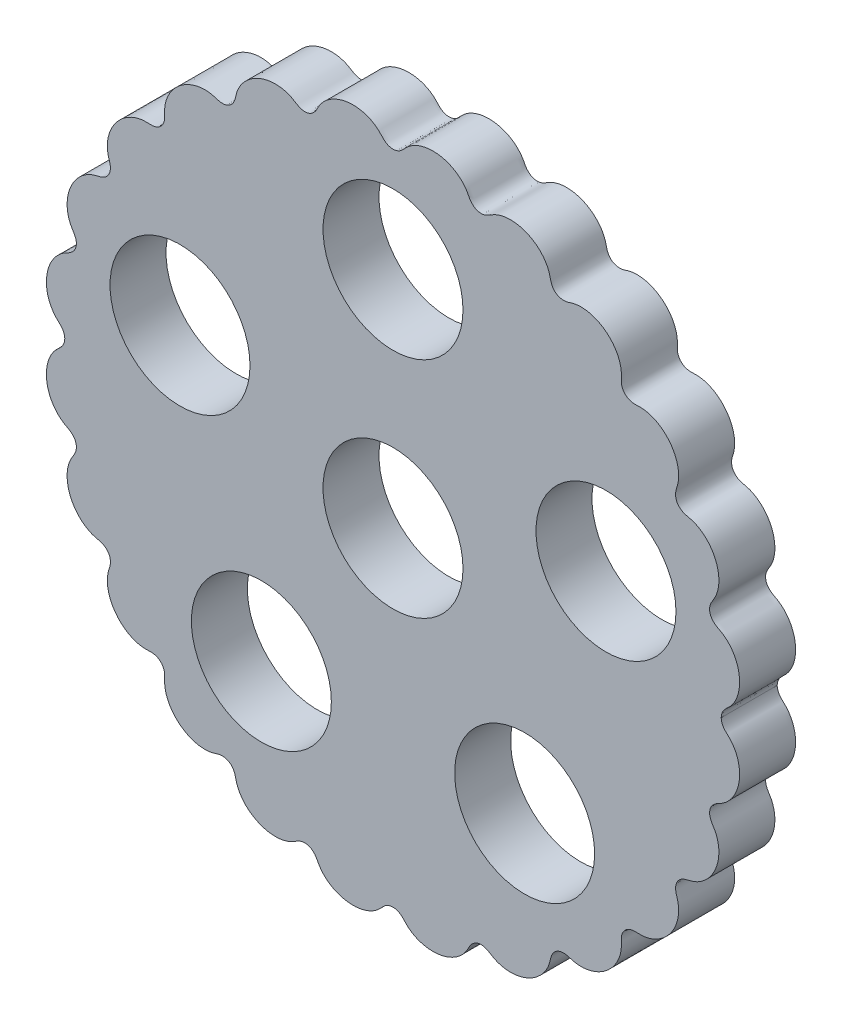
SolidWorks part; units mm, degrees
ref_plane "Plan de face" through (0, 0, 0) normal (0, 0, 1) x (1, 0, 0)
ref_plane "Plan de dessus" through (0, 0, 0) normal (0, 1, 0) x (1, 0, 0)
ref_plane "Plan de droite" through (0, 0, 0) normal (1, 0, 0) x (0, 0, -1)
sketch "Esquisse1" plane through (0, 0, 0) normal (0, 0, 1) x (1, 0, 0)
  line L0 (-1000, 0) -> (49000, 0) construction
  spline S0 degree 4 poles (22.9955, 6.6042) (22.9643, 6.5397) (22.914, 6.4032) (22.9023, 6.1862) (23.0214, 5.9244) (23.2219, 5.7605) (23.4288, 5.659) (23.6594, 5.5306) (23.9059, 5.3649) (24.1666, 5.1353) (24.4254, 4.835) (24.6422, 4.5029) (24.8162, 4.1468) (24.946, 3.7722) (25.0308, 3.385) (25.0698, 2.9906) (25.0624, 2.5943) (25.0079, 2.2017) (24.9068, 1.8224) (24.7781, 1.5066) (24.64, 1.2523) (24.5081, 1.0548) (24.3917, 0.9046) (24.2647, 0.7631) (24.1289, 0.6302) (24.012, 0.5251) (23.9248, 0.4355) (23.8688, 0.3622) (23.8363, 0.3122) (23.8082, 0.2597) (23.7852, 0.2044) (23.7697, 0.1547) (23.76, 0.1121) (23.7533, 0.0661) (23.7501, 0.0228) (23.7495, -0.004) (23.7513, -0.04) (23.7542, -0.0715) (23.7595, -0.1093) (23.7688, -0.1512) (23.7835, -0.1997) (23.8056, -0.2538) (23.8324, -0.3054) (23.8635, -0.3546) (23.9194, -0.4297) (24.009, -0.5227) (24.1313, -0.6322) (24.2737, -0.7721) (24.4392, -0.959) (24.6145, -1.2025) (24.7855, -1.5135) (24.9316, -1.8961) (25.0271, -2.299) (25.0708, -2.7153) (25.0622, -3.1311) (25.0033, -3.5401) (24.8958, -3.9363) (24.7419, -4.314) (24.5445, -4.6645) (24.307, -4.9822) (24.0331, -5.2614) (23.7654, -5.4667) (23.5164, -5.6129) (23.2956, -5.7243) (23.1195, -5.8363) (22.9763, -6.0087) (22.9044, -6.234) (22.925, -6.462) (23.0164, -6.6581) (23.1266, -6.8267) (23.2244, -6.9889) (23.3341, -7.1984) (23.4412, -7.4619) (23.5336, -7.7957) (23.5876, -8.2004) (23.5865, -8.623) (23.5267, -9.0558) (23.3808, -9.5868) (23.1436, -10.0885) (22.8209, -10.5434) (22.4327, -10.9196) (22.1006, -11.1627) (21.7948, -11.3267) (21.5321, -11.4304) (21.3065, -11.4954) (21.1232, -11.5381) (20.9306, -11.5808) (20.7385, -11.6689) (20.5325, -11.8672) (20.4495, -12.16) (20.5219, -12.4298) (20.6167, -12.7241) (20.6818, -13.0067) (20.7176, -13.3406) (20.7046, -13.7295) (20.6405, -14.1156) (20.5273, -14.4945) (20.3673, -14.8595) (20.1602, -15.2112) (19.9061, -15.5428) (19.6059, -15.8469) (19.261, -16.115) (18.8955, -16.3273) (18.5181, -16.4829) (18.1828, -16.5697) (17.9011, -16.6087) (17.6647, -16.6185) (17.4754, -16.6149) (17.2743, -16.6037) (17.0588, -16.6226) (16.851, -16.7187) (16.6918, -16.8937) (16.6141, -17.104) (16.6052, -17.3124) (16.6191, -17.5593) (16.617, -17.8481) (16.5731, -18.1826) (16.4683, -18.5594) (16.3118, -18.9239) (16.107, -19.2701) (15.8569, -19.5923) (15.5674, -19.8834) (15.2427, -20.1389) (14.8869, -20.3543) (14.5046, -20.5246) (14.1078, -20.6433) (13.7035, -20.7081) (13.2985, -20.7166) (12.9508, -20.673) (12.6603, -20.5981) (12.4161, -20.517) (12.2029, -20.4723) (11.9744, -20.5019) (11.768, -20.6211) (11.6281, -20.8042) (11.5602, -21.0112) (11.5084, -21.2632) (11.428, -21.5523) (11.2919, -21.8752) (11.082, -22.2216) (10.8237, -22.5394) (10.5226, -22.8236) (10.1839, -23.0696) (9.8195, -23.2701) (9.4358, -23.4235) (9.039, -23.5286) (8.6349, -23.5841) (8.2327, -23.5884) (7.8388, -23.5416) (7.4601, -23.444) (7.1484, -23.3148) (6.8973, -23.1723) (6.6904, -23.0367) (6.5054, -22.9402) (6.2844, -22.9024) (6.0534, -22.9528) (5.8662, -23.0846) (5.7421, -23.2618) (5.6512, -23.4416) (5.5596, -23.6073) (5.4331, -23.8072) (5.2584, -24.0316) (5.0155, -24.2786) (4.6921, -24.5276) (4.2308, -24.7924) (3.7121, -24.9769) (3.1672, -25.0695) (2.6142, -25.0665) (2.1723, -25.0046) (1.7597, -24.8871) (1.3831, -24.721) (1.0882, -24.5382) (0.867, -24.3625) (0.6979, -24.1997) (0.5693, -24.0623) (0.436, -23.9168) (0.2637, -23.7945) (-0.011, -23.7153) (-0.3061, -23.7898) (-0.5036, -23.9874) (-0.7111, -24.2166) (-0.9232, -24.4143) (-1.1945, -24.6122) (-1.5378, -24.7955) (-1.9042, -24.933) (-2.289, -25.0244) (-2.6851, -25.0684) (-3.0932, -25.0648) (-3.5074, -25.0106) (-3.9209, -24.9026) (-4.3256, -24.738) (-4.6921, -24.5276) (-5.0155, -24.2786) (-5.2584, -24.0316) (-5.4331, -23.8072) (-5.5596, -23.6073) (-5.6512, -23.4416) (-5.7421, -23.2618) (-5.8662, -23.0846) (-6.0534, -22.9528) (-6.2844, -22.9024) (-6.5054, -22.9402) (-6.6904, -23.0367) (-6.8973, -23.1723) (-7.1484, -23.3148) (-7.4601, -23.444) (-7.8388, -23.5416) (-8.2327, -23.5884) (-8.6349, -23.5841) (-9.039, -23.5286) (-9.4358, -23.4235) (-9.8195, -23.2701) (-10.1839, -23.0696) (-10.5226, -22.8236) (-10.8237, -22.5394) (-11.082, -22.2216) (-11.2919, -21.8752) (-11.428, -21.5523) (-11.5084, -21.2632) (-11.5602, -21.0112) (-11.6281, -20.8042) (-11.768, -20.6211) (-11.9744, -20.5019) (-12.2029, -20.4723) (-12.4161, -20.517) (-12.6603, -20.5981) (-12.9508, -20.673) (-13.2985, -20.7166) (-13.7035, -20.7081) (-14.1078, -20.6433) (-14.6048, -20.4946) (-15.1642, -20.2163) (-15.6552, -19.8308) (-16.055, -19.3579) (-16.3118, -18.9239) (-16.4683, -18.5594) (-16.5731, -18.1826) (-16.617, -17.8481) (-16.6191, -17.5593) (-16.6052, -17.3124) (-16.6141, -17.104) (-16.6918, -16.8937) (-16.851, -16.7187) (-17.0588, -16.6226) (-17.2743, -16.6037) (-17.4754, -16.6149) (-17.6647, -16.6185) (-17.9011, -16.6087) (-18.1828, -16.5697) (-18.5181, -16.4829) (-18.8955, -16.3273) (-19.261, -16.1151) (-19.6059, -15.8469) (-19.9061, -15.5428) (-20.1602, -15.2112) (-20.3673, -14.8595) (-20.5273, -14.4945) (-20.6405, -14.1156) (-20.7046, -13.7294) (-20.7175, -13.3407) (-20.6818, -13.0066) (-20.6166, -12.7243) (-20.522, -12.4295) (-20.4494, -12.1605) (-20.5243, -11.8962) (-20.683, -11.7227) (-20.8176, -11.632) (-20.958, -11.5755) (-21.1234, -11.5373) (-21.3064, -11.4958) (-21.5321, -11.4302) (-21.7948, -11.3268) (-22.1006, -11.1626) (-22.4327, -10.9196) (-22.7408, -10.6211) (-23.0153, -10.2693) (-23.2393, -9.8862) (-23.4104, -9.4792) (-23.5267, -9.0558) (-23.5865, -8.623) (-23.5876, -8.2004) (-23.5336, -7.7957) (-23.4412, -7.4619) (-23.3341, -7.1984) (-23.2244, -6.9889) (-23.1266, -6.8267) (-23.0164, -6.6581) (-22.925, -6.462) (-22.9044, -6.234) (-22.9763, -6.0087) (-23.1195, -5.8363) (-23.2956, -5.7243) (-23.5164, -5.6129) (-23.7654, -5.4667) (-24.0331, -5.2614) (-24.307, -4.9822) (-24.5445, -4.6645) (-24.7419, -4.314) (-24.8958, -3.9363) (-25.0033, -3.5401) (-25.0622, -3.1311) (-25.0708, -2.7153) (-25.0271, -2.299) (-24.9316, -1.8961) (-24.7855, -1.5135) (-24.6145, -1.2025) (-24.4393, -0.959) (-24.2737, -0.7721) (-24.1313, -0.6321) (-23.9982, -0.5131) (-23.8995, -0.4084) (-23.8391, -0.3182) (-23.8055, -0.2539) (-23.7835, -0.1997) (-23.7688, -0.1512) (-23.7595, -0.1093) (-23.7542, -0.0715) (-23.7513, -0.04) (-23.7495, -0.0037) (-23.7502, 0.0234) (-23.7534, 0.0677) (-23.7604, 0.1144) (-23.7705, 0.1578) (-23.7867, 0.2087) (-23.8107, 0.2649) (-23.8399, 0.3183) (-23.8736, 0.369) (-23.9317, 0.4432) (-24.0215, 0.5339) (-24.141, 0.6413) (-24.279, 0.7779) (-24.4075, 0.9235) (-24.5249, 1.0783) (-24.6575, 1.2816) (-24.7976, 1.5478) (-24.9275, 1.8824) (-25.0256, 2.2876) (-25.071, 2.7111) (-25.0623, 3.1368) (-25.0002, 3.5582) (-24.8859, 3.9683) (-24.7199, 4.3608) (-24.4999, 4.7349) (-24.2231, 5.0813) (-23.9331, 5.3469) (-23.6469, 5.5411) (-23.3456, 5.7009) (-23.0735, 5.8417) (-22.8982, 6.1368) (-22.9147, 6.4027) (-22.9638, 6.54) (-22.9956, 6.6042) knots 0 0 0 0 0 0.002762 0.005524 0.008057 0.010589 0.012487 0.014385 0.018181 0.021977 0.025773 0.029569 0.033366 0.037162 0.040959 0.044755 0.048552 0.052348 0.056144 0.059791 0.061614 0.063437 0.06526 0.067083 0.068906 0.070729 0.071301 0.071873 0.072445 0.073016 0.073588 0.07416 0.074446 0.074731 0.075303 0.075582 0.075861 0.07614 0.076419 0.076977 0.077535 0.078093 0.078652 0.07921 0.079768 0.081683 0.083599 0.085515 0.08743 0.091261 0.095093 0.099101 0.103109 0.107118 0.111126 0.115032 0.118938 0.122843 0.126749 0.130438 0.134127 0.137815 0.13966 0.141504 0.143638 0.145771 0.148068 0.150364 0.15218 0.153996 0.155812 0.157628 0.16126 0.164892 0.169075 0.173257 0.177439 0.181621 0.190162 0.194433 0.198704 0.20231 0.205917 0.20772 0.209523 0.211327 0.21313 0.215313 0.217496 0.222107 0.223949 0.225791 0.229476 0.23316 0.236844 0.240662 0.24448 0.248298 0.252116 0.256299 0.260481 0.264663 0.268845 0.272477 0.276109 0.277925 0.279741 0.281557 0.283373 0.28567 0.287966 0.2901 0.292233 0.294078 0.295922 0.299611 0.3033 0.306988 0.310894 0.3148 0.318706 0.322612 0.32662 0.330628 0.334637 0.338645 0.342476 0.346307 0.350139 0.352054 0.35397 0.356202 0.358434 0.360667 0.362899 0.364815 0.36673 0.370561 0.374393 0.378224 0.382232 0.386241 0.390249 0.394257 0.398163 0.402069 0.405975 0.40988 0.413569 0.417258 0.420947 0.422791 0.424635 0.426769 0.428902 0.431199 0.433495 0.435311 0.437127 0.438943 0.440759 0.444392 0.448024 0.452206 0.456388 0.464752 0.469023 0.473294 0.477564 0.481835 0.485441 0.489048 0.490851 0.492655 0.494458 0.496261 0.498444 0.500627 0.505239 0.507081 0.508923 0.512607 0.516291 0.519975 0.523793 0.527611 0.53143 0.535248 0.53943 0.543612 0.547794 0.551976 0.555609 0.559241 0.561057 0.562873 0.564689 0.566505 0.568801 0.571098 0.573231 0.575365 0.577209 0.579053 0.582742 0.586431 0.59012 0.594025 0.597931 0.601837 0.605743 0.609751 0.61376 0.617768 0.621776 0.625607 0.629439 0.63327 0.635186 0.637101 0.639333 0.641566 0.643798 0.64603 0.647946 0.649861 0.653693 0.657524 0.661355 0.665364 0.669372 0.677388 0.6852 0.689106 0.693012 0.6967 0.700389 0.704078 0.705922 0.707767 0.7099 0.712034 0.71433 0.716627 0.718443 0.720259 0.722075 0.723891 0.727523 0.731155 0.735337 0.739519 0.743701 0.747884 0.751702 0.75552 0.759338 0.763156 0.76684 0.770525 0.774209 0.776051 0.777893 0.782504 0.784687 0.785779 0.78687 0.788673 0.790477 0.79228 0.794083 0.79769 0.801296 0.805567 0.809838 0.814108 0.818379 0.822561 0.826743 0.830926 0.835108 0.83874 0.842372 0.844188 0.846004 0.84782 0.849636 0.851932 0.854229 0.856362 0.858496 0.86034 0.862185 0.865873 0.869562 0.873251 0.877157 0.881063 0.884968 0.888874 0.892882 0.896891 0.900899 0.904907 0.908739 0.91257 0.914486 0.916401 0.918317 0.920232 0.921349 0.921907 0.922465 0.923023 0.923581 0.92386 0.924139 0.924418 0.924697 0.925281 0.925573 0.925865 0.926449 0.927033 0.927617 0.928201 0.928785 0.929369 0.931232 0.933095 0.934957 0.93682 0.938683 0.940546 0.944272 0.94835 0.952428 0.956506 0.960584 0.964661 0.968739 0.972817 0.976894 0.98129 0.985685 0.987883 0.99008 0.994476 0.997238 1 1 1 1 1 construction
  spline S1 degree 4 poles (23.75, 0) (23.75, -0.0062) (23.7502, -0.0186) (23.7513, -0.04) (23.7542, -0.0715) (23.7595, -0.1093) (23.7688, -0.1512) (23.7835, -0.1997) (23.8056, -0.2538) (23.8324, -0.3054) (23.8635, -0.3546) (23.9194, -0.4297) (24.009, -0.5227) (24.1313, -0.6322) (24.2737, -0.7721) (24.4392, -0.959) (24.6145, -1.2025) (24.7855, -1.5135) (24.9316, -1.8961) (25.0271, -2.299) (25.0708, -2.7153) (25.0622, -3.1311) (25.0033, -3.5401) (24.8958, -3.9363) (24.7419, -4.314) (24.5445, -4.6645) (24.307, -4.9822) (24.0331, -5.2614) (23.7654, -5.4667) (23.5164, -5.6129) (23.2956, -5.7243) (23.1195, -5.8363) (22.9763, -6.0087) (22.9044, -6.234) (22.925, -6.462) (23.0164, -6.6581) (23.1266, -6.8267) (23.2244, -6.9889) (23.3341, -7.1984) (23.4412, -7.4619) (23.5336, -7.7957) (23.5876, -8.2004) (23.5865, -8.623) (23.5267, -9.0558) (23.3808, -9.5868) (23.1436, -10.0885) (22.8209, -10.5434) (22.4327, -10.9196) (22.1006, -11.1627) (21.7948, -11.3267) (21.5321, -11.4304) (21.3065, -11.4954) (21.1232, -11.5381) (20.9306, -11.5808) (20.7385, -11.6689) (20.5325, -11.8672) (20.4495, -12.16) (20.5219, -12.4298) (20.6167, -12.7241) (20.6818, -13.0067) (20.7176, -13.3406) (20.7046, -13.7295) (20.6405, -14.1156) (20.5273, -14.4945) (20.3673, -14.8595) (20.1602, -15.2112) (19.9061, -15.5428) (19.6059, -15.8469) (19.261, -16.115) (18.8955, -16.3273) (18.5181, -16.4829) (18.1828, -16.5697) (17.9011, -16.6087) (17.6647, -16.6185) (17.4754, -16.6149) (17.2743, -16.6037) (17.0588, -16.6226) (16.851, -16.7187) (16.6918, -16.8937) (16.6141, -17.104) (16.6052, -17.3124) (16.6191, -17.5593) (16.617, -17.8481) (16.5731, -18.1826) (16.4683, -18.5594) (16.3118, -18.9239) (16.107, -19.2701) (15.8569, -19.5923) (15.5674, -19.8834) (15.2427, -20.1389) (14.8869, -20.3543) (14.5046, -20.5246) (14.1078, -20.6433) (13.7035, -20.7081) (13.2985, -20.7166) (12.9508, -20.673) (12.6603, -20.5981) (12.4161, -20.517) (12.2029, -20.4723) (11.9744, -20.5019) (11.768, -20.6211) (11.6281, -20.8042) (11.5602, -21.0112) (11.5084, -21.2632) (11.428, -21.5523) (11.2919, -21.8752) (11.082, -22.2216) (10.8237, -22.5394) (10.5226, -22.8236) (10.1839, -23.0696) (9.8195, -23.2701) (9.4358, -23.4235) (9.039, -23.5286) (8.6349, -23.5841) (8.2327, -23.5884) (7.8388, -23.5416) (7.4601, -23.444) (7.1484, -23.3148) (6.8973, -23.1723) (6.6904, -23.0367) (6.5054, -22.9402) (6.2844, -22.9024) (6.0534, -22.9528) (5.8662, -23.0846) (5.7421, -23.2618) (5.6512, -23.4416) (5.5596, -23.6073) (5.4331, -23.8072) (5.2584, -24.0316) (5.0155, -24.2786) (4.6921, -24.5276) (4.2308, -24.7924) (3.7121, -24.9769) (3.1672, -25.0695) (2.6142, -25.0665) (2.1723, -25.0046) (1.7597, -24.8871) (1.3831, -24.721) (1.0882, -24.5382) (0.867, -24.3625) (0.6979, -24.1997) (0.5693, -24.0623) (0.436, -23.9168) (0.2637, -23.7945) (-0.011, -23.7153) (-0.3061, -23.7898) (-0.5036, -23.9874) (-0.7111, -24.2166) (-0.9232, -24.4143) (-1.1945, -24.6122) (-1.5378, -24.7955) (-1.9042, -24.933) (-2.289, -25.0244) (-2.6851, -25.0684) (-3.0932, -25.0648) (-3.5074, -25.0106) (-3.9209, -24.9026) (-4.3256, -24.738) (-4.6921, -24.5276) (-5.0155, -24.2786) (-5.2584, -24.0316) (-5.4331, -23.8072) (-5.5596, -23.6073) (-5.6512, -23.4416) (-5.7421, -23.2618) (-5.8662, -23.0846) (-6.0534, -22.9528) (-6.2844, -22.9024) (-6.5054, -22.9402) (-6.6904, -23.0367) (-6.8973, -23.1723) (-7.1484, -23.3148) (-7.4601, -23.444) (-7.8388, -23.5416) (-8.2327, -23.5884) (-8.6349, -23.5841) (-9.039, -23.5286) (-9.4358, -23.4235) (-9.8195, -23.2701) (-10.1839, -23.0696) (-10.5226, -22.8236) (-10.8237, -22.5394) (-11.082, -22.2216) (-11.2919, -21.8752) (-11.428, -21.5523) (-11.5084, -21.2632) (-11.5602, -21.0112) (-11.6281, -20.8042) (-11.768, -20.6211) (-11.9744, -20.5019) (-12.2029, -20.4723) (-12.4161, -20.517) (-12.6603, -20.5981) (-12.9508, -20.673) (-13.2985, -20.7166) (-13.7035, -20.7081) (-14.1078, -20.6433) (-14.6048, -20.4946) (-15.1642, -20.2163) (-15.6552, -19.8308) (-16.055, -19.3579) (-16.3118, -18.9239) (-16.4683, -18.5594) (-16.5731, -18.1826) (-16.617, -17.8481) (-16.6191, -17.5593) (-16.6052, -17.3124) (-16.6141, -17.104) (-16.6918, -16.8937) (-16.851, -16.7187) (-17.0588, -16.6226) (-17.2743, -16.6037) (-17.4754, -16.6149) (-17.6647, -16.6185) (-17.9011, -16.6087) (-18.1828, -16.5697) (-18.5181, -16.4829) (-18.8955, -16.3273) (-19.261, -16.1151) (-19.6059, -15.8469) (-19.9061, -15.5428) (-20.1602, -15.2112) (-20.3673, -14.8595) (-20.5273, -14.4945) (-20.6405, -14.1156) (-20.7046, -13.7294) (-20.7175, -13.3407) (-20.6818, -13.0066) (-20.6166, -12.7243) (-20.522, -12.4295) (-20.4494, -12.1605) (-20.5243, -11.8962) (-20.683, -11.7227) (-20.8176, -11.632) (-20.958, -11.5755) (-21.1234, -11.5373) (-21.3064, -11.4958) (-21.5321, -11.4302) (-21.7948, -11.3268) (-22.1006, -11.1626) (-22.4327, -10.9196) (-22.7408, -10.6211) (-23.0153, -10.2693) (-23.2393, -9.8862) (-23.4104, -9.4792) (-23.5267, -9.0558) (-23.5865, -8.623) (-23.5876, -8.2004) (-23.5336, -7.7957) (-23.4412, -7.4619) (-23.3341, -7.1984) (-23.2244, -6.9889) (-23.1266, -6.8267) (-23.0164, -6.6581) (-22.925, -6.462) (-22.9044, -6.234) (-22.9763, -6.0087) (-23.1195, -5.8363) (-23.2956, -5.7243) (-23.5164, -5.6129) (-23.7654, -5.4667) (-24.0331, -5.2614) (-24.307, -4.9822) (-24.5445, -4.6645) (-24.7419, -4.314) (-24.8958, -3.9363) (-25.0033, -3.5401) (-25.0622, -3.1311) (-25.0708, -2.7153) (-25.0271, -2.299) (-24.9316, -1.8961) (-24.7855, -1.5135) (-24.6145, -1.2025) (-24.4393, -0.959) (-24.2737, -0.7721) (-24.1313, -0.6321) (-23.9982, -0.5131) (-23.8995, -0.4084) (-23.8391, -0.3182) (-23.8055, -0.2539) (-23.7835, -0.1997) (-23.7688, -0.1512) (-23.7595, -0.1093) (-23.7542, -0.0715) (-23.7513, -0.04) (-23.7502, -0.0186) (-23.75, -0.0062) (-23.75, 0) knots 0.075303 0.075303 0.075303 0.075303 0.075303 0.075582 0.075861 0.07614 0.076419 0.076977 0.077535 0.078093 0.078652 0.07921 0.079768 0.081683 0.083599 0.085515 0.08743 0.091261 0.095093 0.099101 0.103109 0.107118 0.111126 0.115032 0.118938 0.122843 0.126749 0.130438 0.134127 0.137815 0.13966 0.141504 0.143638 0.145771 0.148068 0.150364 0.15218 0.153996 0.155812 0.157628 0.16126 0.164892 0.169075 0.173257 0.177439 0.181621 0.190162 0.194433 0.198704 0.20231 0.205917 0.20772 0.209523 0.211327 0.21313 0.215313 0.217496 0.222107 0.223949 0.225791 0.229476 0.23316 0.236844 0.240662 0.24448 0.248298 0.252116 0.256299 0.260481 0.264663 0.268845 0.272477 0.276109 0.277925 0.279741 0.281557 0.283373 0.28567 0.287966 0.2901 0.292233 0.294078 0.295922 0.299611 0.3033 0.306988 0.310894 0.3148 0.318706 0.322612 0.32662 0.330628 0.334637 0.338645 0.342476 0.346307 0.350139 0.352054 0.35397 0.356202 0.358434 0.360667 0.362899 0.364815 0.36673 0.370561 0.374393 0.378224 0.382232 0.386241 0.390249 0.394257 0.398163 0.402069 0.405975 0.40988 0.413569 0.417258 0.420947 0.422791 0.424635 0.426769 0.428902 0.431199 0.433495 0.435311 0.437127 0.438943 0.440759 0.444392 0.448024 0.452206 0.456388 0.464752 0.469023 0.473294 0.477564 0.481835 0.485441 0.489048 0.490851 0.492655 0.494458 0.496261 0.498444 0.500627 0.505239 0.507081 0.508923 0.512607 0.516291 0.519975 0.523793 0.527611 0.53143 0.535248 0.53943 0.543612 0.547794 0.551976 0.555609 0.559241 0.561057 0.562873 0.564689 0.566505 0.568801 0.571098 0.573231 0.575365 0.577209 0.579053 0.582742 0.586431 0.59012 0.594025 0.597931 0.601837 0.605743 0.609751 0.61376 0.617768 0.621776 0.625607 0.629439 0.63327 0.635186 0.637101 0.639333 0.641566 0.643798 0.64603 0.647946 0.649861 0.653693 0.657524 0.661355 0.665364 0.669372 0.677388 0.6852 0.689106 0.693012 0.6967 0.700389 0.704078 0.705922 0.707767 0.7099 0.712034 0.71433 0.716627 0.718443 0.720259 0.722075 0.723891 0.727523 0.731155 0.735337 0.739519 0.743701 0.747884 0.751702 0.75552 0.759338 0.763156 0.76684 0.770525 0.774209 0.776051 0.777893 0.782504 0.784687 0.785779 0.78687 0.788673 0.790477 0.79228 0.794083 0.79769 0.801296 0.805567 0.809838 0.814108 0.818379 0.822561 0.826743 0.830926 0.835108 0.83874 0.842372 0.844188 0.846004 0.84782 0.849636 0.851932 0.854229 0.856362 0.858496 0.86034 0.862185 0.865873 0.869562 0.873251 0.877157 0.881063 0.884968 0.888874 0.892882 0.896891 0.900899 0.904907 0.908739 0.91257 0.914486 0.916401 0.918317 0.920232 0.921349 0.921907 0.922465 0.923023 0.923581 0.92386 0.924139 0.924418 0.924697 0.924697 0.924697 0.924697 0.924697 construction
  spline S2 degree 4 poles (23.75, 0) (23.75, 0.0062) (23.7502, 0.0186) (23.7513, 0.04) (23.7542, 0.0715) (23.7595, 0.1093) (23.7688, 0.1512) (23.7835, 0.1997) (23.8056, 0.2538) (23.8324, 0.3054) (23.8635, 0.3546) (23.9194, 0.4297) (24.009, 0.5227) (24.1313, 0.6322) (24.2737, 0.7721) (24.4392, 0.959) (24.6145, 1.2025) (24.7855, 1.5135) (24.9316, 1.8961) (25.0271, 2.299) (25.0708, 2.7153) (25.0622, 3.1311) (25.0033, 3.5401) (24.8958, 3.9363) (24.7419, 4.314) (24.5445, 4.6645) (24.307, 4.9822) (24.0331, 5.2614) (23.7654, 5.4667) (23.5164, 5.6129) (23.2956, 5.7243) (23.1195, 5.8363) (22.9763, 6.0087) (22.9044, 6.234) (22.925, 6.462) (23.0164, 6.6581) (23.1266, 6.8267) (23.2244, 6.9889) (23.3341, 7.1984) (23.4412, 7.4619) (23.5336, 7.7957) (23.5876, 8.2004) (23.5865, 8.623) (23.5267, 9.0558) (23.3808, 9.5868) (23.1436, 10.0885) (22.8209, 10.5434) (22.4327, 10.9196) (22.1006, 11.1627) (21.7948, 11.3267) (21.5321, 11.4304) (21.3065, 11.4954) (21.1232, 11.5381) (20.9306, 11.5808) (20.7385, 11.6689) (20.5325, 11.8672) (20.4495, 12.16) (20.5219, 12.4298) (20.6167, 12.7241) (20.6818, 13.0067) (20.7176, 13.3406) (20.7046, 13.7295) (20.6405, 14.1156) (20.5273, 14.4945) (20.3673, 14.8595) (20.1602, 15.2112) (19.9061, 15.5428) (19.6059, 15.8469) (19.261, 16.115) (18.8955, 16.3273) (18.5181, 16.4829) (18.1828, 16.5697) (17.9011, 16.6087) (17.6647, 16.6185) (17.4754, 16.6149) (17.2743, 16.6037) (17.0588, 16.6226) (16.851, 16.7187) (16.6918, 16.8937) (16.6141, 17.104) (16.6052, 17.3124) (16.6191, 17.5593) (16.617, 17.8481) (16.5731, 18.1826) (16.4683, 18.5594) (16.3118, 18.9239) (16.107, 19.2701) (15.8569, 19.5923) (15.5674, 19.8834) (15.2427, 20.1389) (14.8869, 20.3543) (14.5046, 20.5246) (14.1078, 20.6433) (13.7035, 20.7081) (13.2985, 20.7166) (12.9508, 20.673) (12.6603, 20.5981) (12.4161, 20.517) (12.2029, 20.4723) (11.9744, 20.5019) (11.768, 20.6211) (11.6281, 20.8042) (11.5602, 21.0112) (11.5084, 21.2632) (11.428, 21.5523) (11.2919, 21.8752) (11.082, 22.2216) (10.8237, 22.5394) (10.5226, 22.8236) (10.1839, 23.0696) (9.8195, 23.2701) (9.4358, 23.4235) (9.039, 23.5286) (8.6349, 23.5841) (8.2327, 23.5884) (7.8388, 23.5416) (7.4601, 23.444) (7.1484, 23.3148) (6.8973, 23.1723) (6.6904, 23.0367) (6.5054, 22.9402) (6.2844, 22.9024) (6.0534, 22.9528) (5.8662, 23.0846) (5.7421, 23.2618) (5.6512, 23.4416) (5.5596, 23.6073) (5.4331, 23.8072) (5.2584, 24.0316) (5.0155, 24.2786) (4.6921, 24.5276) (4.2308, 24.7924) (3.7121, 24.9769) (3.1672, 25.0695) (2.6142, 25.0665) (2.1723, 25.0046) (1.7597, 24.8871) (1.3831, 24.721) (1.0882, 24.5382) (0.867, 24.3625) (0.6979, 24.1997) (0.5693, 24.0623) (0.436, 23.9168) (0.2637, 23.7945) (-0.011, 23.7153) (-0.3061, 23.7898) (-0.5036, 23.9874) (-0.7111, 24.2166) (-0.9232, 24.4143) (-1.1945, 24.6122) (-1.5378, 24.7955) (-1.9042, 24.933) (-2.289, 25.0244) (-2.6851, 25.0684) (-3.0932, 25.0648) (-3.5074, 25.0106) (-3.9209, 24.9026) (-4.3256, 24.738) (-4.6921, 24.5276) (-5.0155, 24.2786) (-5.2584, 24.0316) (-5.4331, 23.8072) (-5.5596, 23.6073) (-5.6512, 23.4416) (-5.7421, 23.2618) (-5.8662, 23.0846) (-6.0534, 22.9528) (-6.2844, 22.9024) (-6.5054, 22.9402) (-6.6904, 23.0367) (-6.8973, 23.1723) (-7.1484, 23.3148) (-7.4601, 23.444) (-7.8388, 23.5416) (-8.2327, 23.5884) (-8.6349, 23.5841) (-9.039, 23.5286) (-9.4358, 23.4235) (-9.8195, 23.2701) (-10.1839, 23.0696) (-10.5226, 22.8236) (-10.8237, 22.5394) (-11.082, 22.2216) (-11.2919, 21.8752) (-11.428, 21.5523) (-11.5084, 21.2632) (-11.5602, 21.0112) (-11.6281, 20.8042) (-11.768, 20.6211) (-11.9744, 20.5019) (-12.2029, 20.4723) (-12.4161, 20.517) (-12.6603, 20.5981) (-12.9508, 20.673) (-13.2985, 20.7166) (-13.7035, 20.7081) (-14.1078, 20.6433) (-14.6048, 20.4946) (-15.1642, 20.2163) (-15.6552, 19.8308) (-16.055, 19.3579) (-16.3118, 18.9239) (-16.4683, 18.5594) (-16.5731, 18.1826) (-16.617, 17.8481) (-16.6191, 17.5593) (-16.6052, 17.3124) (-16.6141, 17.104) (-16.6918, 16.8937) (-16.851, 16.7187) (-17.0588, 16.6226) (-17.2743, 16.6037) (-17.4754, 16.6149) (-17.6647, 16.6185) (-17.9011, 16.6087) (-18.1828, 16.5697) (-18.5181, 16.4829) (-18.8955, 16.3273) (-19.261, 16.1151) (-19.6059, 15.8469) (-19.9061, 15.5428) (-20.1602, 15.2112) (-20.3673, 14.8595) (-20.5273, 14.4945) (-20.6405, 14.1156) (-20.7046, 13.7294) (-20.7175, 13.3407) (-20.6818, 13.0066) (-20.6166, 12.7243) (-20.522, 12.4295) (-20.4494, 12.1605) (-20.5243, 11.8962) (-20.683, 11.7227) (-20.8176, 11.632) (-20.958, 11.5755) (-21.1234, 11.5373) (-21.3064, 11.4958) (-21.5321, 11.4302) (-21.7948, 11.3268) (-22.1006, 11.1626) (-22.4327, 10.9196) (-22.7408, 10.6211) (-23.0153, 10.2693) (-23.2393, 9.8862) (-23.4104, 9.4792) (-23.5267, 9.0558) (-23.5865, 8.623) (-23.5876, 8.2004) (-23.5336, 7.7957) (-23.4412, 7.4619) (-23.3341, 7.1984) (-23.2244, 6.9889) (-23.1266, 6.8267) (-23.0164, 6.6581) (-22.925, 6.462) (-22.9044, 6.234) (-22.9763, 6.0087) (-23.1195, 5.8363) (-23.2956, 5.7243) (-23.5164, 5.6129) (-23.7654, 5.4667) (-24.0331, 5.2614) (-24.307, 4.9822) (-24.5445, 4.6645) (-24.7419, 4.314) (-24.8958, 3.9363) (-25.0033, 3.5401) (-25.0622, 3.1311) (-25.0708, 2.7153) (-25.0271, 2.299) (-24.9316, 1.8961) (-24.7855, 1.5135) (-24.6145, 1.2025) (-24.4393, 0.959) (-24.2737, 0.7721) (-24.1313, 0.6321) (-23.9982, 0.5131) (-23.8995, 0.4084) (-23.8391, 0.3182) (-23.8055, 0.2539) (-23.7835, 0.1997) (-23.7688, 0.1512) (-23.7595, 0.1093) (-23.7542, 0.0715) (-23.7513, 0.04) (-23.7502, 0.0186) (-23.75, 0.0062) (-23.75, 0) knots 0.075303 0.075303 0.075303 0.075303 0.075303 0.075582 0.075861 0.07614 0.076419 0.076977 0.077535 0.078093 0.078652 0.07921 0.079768 0.081683 0.083599 0.085515 0.08743 0.091261 0.095093 0.099101 0.103109 0.107118 0.111126 0.115032 0.118938 0.122843 0.126749 0.130438 0.134127 0.137815 0.13966 0.141504 0.143638 0.145771 0.148068 0.150364 0.15218 0.153996 0.155812 0.157628 0.16126 0.164892 0.169075 0.173257 0.177439 0.181621 0.190162 0.194433 0.198704 0.20231 0.205917 0.20772 0.209523 0.211327 0.21313 0.215313 0.217496 0.222107 0.223949 0.225791 0.229476 0.23316 0.236844 0.240662 0.24448 0.248298 0.252116 0.256299 0.260481 0.264663 0.268845 0.272477 0.276109 0.277925 0.279741 0.281557 0.283373 0.28567 0.287966 0.2901 0.292233 0.294078 0.295922 0.299611 0.3033 0.306988 0.310894 0.3148 0.318706 0.322612 0.32662 0.330628 0.334637 0.338645 0.342476 0.346307 0.350139 0.352054 0.35397 0.356202 0.358434 0.360667 0.362899 0.364815 0.36673 0.370561 0.374393 0.378224 0.382232 0.386241 0.390249 0.394257 0.398163 0.402069 0.405975 0.40988 0.413569 0.417258 0.420947 0.422791 0.424635 0.426769 0.428902 0.431199 0.433495 0.435311 0.437127 0.438943 0.440759 0.444392 0.448024 0.452206 0.456388 0.464752 0.469023 0.473294 0.477564 0.481835 0.485441 0.489048 0.490851 0.492655 0.494458 0.496261 0.498444 0.500627 0.505239 0.507081 0.508923 0.512607 0.516291 0.519975 0.523793 0.527611 0.53143 0.535248 0.53943 0.543612 0.547794 0.551976 0.555609 0.559241 0.561057 0.562873 0.564689 0.566505 0.568801 0.571098 0.573231 0.575365 0.577209 0.579053 0.582742 0.586431 0.59012 0.594025 0.597931 0.601837 0.605743 0.609751 0.61376 0.617768 0.621776 0.625607 0.629439 0.63327 0.635186 0.637101 0.639333 0.641566 0.643798 0.64603 0.647946 0.649861 0.653693 0.657524 0.661355 0.665364 0.669372 0.677388 0.6852 0.689106 0.693012 0.6967 0.700389 0.704078 0.705922 0.707767 0.7099 0.712034 0.71433 0.716627 0.718443 0.720259 0.722075 0.723891 0.727523 0.731155 0.735337 0.739519 0.743701 0.747884 0.751702 0.75552 0.759338 0.763156 0.76684 0.770525 0.774209 0.776051 0.777893 0.782504 0.784687 0.785779 0.78687 0.788673 0.790477 0.79228 0.794083 0.79769 0.801296 0.805567 0.809838 0.814108 0.818379 0.822561 0.826743 0.830926 0.835108 0.83874 0.842372 0.844188 0.846004 0.84782 0.849636 0.851932 0.854229 0.856362 0.858496 0.86034 0.862185 0.865873 0.869562 0.873251 0.877157 0.881063 0.884968 0.888874 0.892882 0.896891 0.900899 0.904907 0.908739 0.91257 0.914486 0.916401 0.918317 0.920232 0.921349 0.921907 0.922465 0.923023 0.923581 0.92386 0.924139 0.924418 0.924697 0.924697 0.924697 0.924697 0.924697 construction
  spline S3 degree 1 poles (23.45, 0) (-23.45, 0) knots 0 0 1 1 construction
  spline S4 degree 1 poles (23.45, 0) (-23.45, 0) knots 0 0 1 1 construction
  spline S5 degree 3 poles (23.45, 0) (23.45, 0.1688) (23.568, 0.5278) (23.8903, 0.8164) (24.1013, 1.0222) (24.3587, 1.3466) (24.5964, 1.8063) (24.7533, 2.417) (24.7783, 3.0489) (24.6745, 3.6737) (24.4451, 4.2626) (24.099, 4.7863) (23.7155, 5.1377) (23.3769, 5.3531) (23.0464, 5.4986) (22.6619, 5.8789) (22.5776, 6.428) (22.7925, 6.8813) (22.9696, 7.1351) (23.1019, 7.4146) (23.2323, 7.8035) (23.304, 8.3209) (23.2521, 8.9496) (23.0707, 9.5562) (22.77, 10.1134) (22.3622, 10.5947) (21.9457, 10.9098) (21.5784, 11.0927) (21.2872, 11.1966) (20.9839, 11.2507) (20.5102, 11.4191) (20.1813, 11.8683) (20.1841, 12.4065) (20.3154, 12.746) (20.4021, 13.1356) (20.4251, 13.6565) (20.2994, 14.2711) (20.0452, 14.8498) (19.6768, 15.365) (19.2123, 15.7942) (18.6695, 16.115) (18.1764, 16.272) (17.7649, 16.3194) (17.4715, 16.3153) (17.0363, 16.2938) (16.5399, 16.54) (16.2939, 17.0362) (16.3151, 17.4714) (16.3195, 17.7647) (16.272, 18.1766) (16.115, 18.6694) (15.7942, 19.2123) (15.365, 19.6768) (14.8498, 20.0452) (14.2711, 20.2994) (13.6562, 20.425) (13.1364, 20.4022) (12.7449, 20.3152) (12.408, 20.1843) (11.8674, 20.1814) (11.4195, 20.5101) (11.251, 20.9821) (11.1968, 21.2872) (11.0925, 21.5785) (10.9099, 21.9455) (10.5946, 22.3622) (10.1134, 22.77) (9.5562, 23.0707) (8.9496, 23.2521) (8.3209, 23.304) (7.8034, 23.2323) (7.4147, 23.1019) (7.135, 22.9696) (6.881, 22.7923) (6.428, 22.5776) (5.8789, 22.662) (5.4987, 23.0462) (5.3534, 23.3764) (5.1376, 23.7157) (4.7864, 24.0989) (4.2626, 24.4451) (3.6737, 24.6745) (3.0489, 24.7783) (2.4169, 24.7533) (1.8063, 24.5964) (1.3466, 24.3586) (1.0223, 24.1015) (0.817, 23.8905) (0.5243, 23.5677) (0, 23.3911) (-0.5244, 23.5679) (-0.8184, 23.891) (-1.0212, 24.1007) (-1.3474, 24.3592) (-1.8061, 24.5962) (-2.417, 24.7534) (-3.0489, 24.7783) (-3.6737, 24.6745) (-4.2626, 24.4451) (-4.7864, 24.0989) (-5.1376, 23.7157) (-5.3534, 23.3764) (-5.4987, 23.0462) (-5.8789, 22.662) (-6.428, 22.5776) (-6.881, 22.7923) (-7.135, 22.9696) (-7.4147, 23.1019) (-7.8034, 23.2323) (-8.3209, 23.304) (-8.9496, 23.2521) (-9.5562, 23.0707) (-10.1134, 22.77) (-10.5946, 22.3622) (-10.9099, 21.9455) (-11.0925, 21.5785) (-11.1968, 21.2872) (-11.251, 20.9821) (-11.4195, 20.5101) (-11.8674, 20.1814) (-12.408, 20.1843) (-12.7449, 20.3152) (-13.1364, 20.4022) (-13.6562, 20.425) (-14.2711, 20.2994) (-14.8498, 20.0452) (-15.365, 19.6768) (-15.7942, 19.2123) (-16.115, 18.6694) (-16.272, 18.1766) (-16.3195, 17.7647) (-16.3151, 17.4714) (-16.2939, 17.0362) (-16.5399, 16.54) (-17.0363, 16.2938) (-17.4715, 16.3153) (-17.7649, 16.3194) (-18.1764, 16.272) (-18.6695, 16.115) (-19.2123, 15.7942) (-19.6768, 15.365) (-20.0452, 14.8498) (-20.2994, 14.2711) (-20.4251, 13.6564) (-20.4021, 13.1357) (-20.3154, 12.7458) (-20.1841, 12.4068) (-20.1814, 11.868) (-20.5097, 11.4197) (-20.9827, 11.251) (-21.2874, 11.1967) (-21.5785, 11.0925) (-21.9455, 10.9099) (-22.3622, 10.5946) (-22.77, 10.1134) (-23.0707, 9.5562) (-23.2521, 8.9496) (-23.304, 8.3209) (-23.2323, 7.8035) (-23.1019, 7.4146) (-22.9696, 7.1351) (-22.7925, 6.8813) (-22.5776, 6.428) (-22.6619, 5.8789) (-23.0464, 5.4986) (-23.3769, 5.3531) (-23.7155, 5.1377) (-24.099, 4.7863) (-24.4451, 4.2626) (-24.6745, 3.6737) (-24.7783, 3.0489) (-24.7533, 2.417) (-24.5964, 1.8063) (-24.3588, 1.3466) (-24.1012, 1.0222) (-23.8905, 0.8166) (-23.5677, 0.5274) (-23.45, 0.1688) (-23.45, 0) knots 0.075303 0.075303 0.075303 0.075303 0.078621 0.081939 0.085257 0.088575 0.095211 0.101847 0.108483 0.115118 0.121754 0.12839 0.135026 0.138344 0.141662 0.14498 0.148298 0.151616 0.154934 0.158252 0.16157 0.168206 0.174841 0.181477 0.188113 0.194749 0.201385 0.204703 0.208021 0.211339 0.214657 0.217975 0.221293 0.224611 0.227929 0.234564 0.2412 0.247836 0.254472 0.261108 0.267744 0.27438 0.277698 0.281016 0.284334 0.287652 0.29097 0.294287 0.297605 0.300923 0.307559 0.314195 0.320831 0.327467 0.334103 0.340739 0.347375 0.350693 0.35401 0.357328 0.360646 0.363964 0.367282 0.3706 0.373918 0.380554 0.38719 0.393826 0.400462 0.407098 0.413733 0.417051 0.420369 0.423687 0.427005 0.430323 0.433641 0.436959 0.440277 0.446913 0.453549 0.460185 0.466821 0.473456 0.480092 0.486728 0.490046 0.493364 0.496682 0.5 0.503318 0.506636 0.509954 0.513272 0.519908 0.526544 0.533179 0.539815 0.546451 0.553087 0.559723 0.563041 0.566359 0.569677 0.572995 0.576313 0.579631 0.582949 0.586267 0.592902 0.599538 0.606174 0.61281 0.619446 0.626082 0.6294 0.632718 0.636036 0.639354 0.642672 0.64599 0.649308 0.652625 0.659261 0.665897 0.672533 0.679169 0.685805 0.692441 0.699077 0.702395 0.705713 0.709031 0.712348 0.715666 0.718984 0.722302 0.72562 0.732256 0.738892 0.745528 0.752164 0.7588 0.765436 0.772071 0.775389 0.778707 0.782025 0.785343 0.788661 0.791979 0.795297 0.798615 0.805251 0.811887 0.818523 0.825159 0.831794 0.83843 0.841748 0.845066 0.848384 0.851702 0.85502 0.858338 0.861656 0.864974 0.87161 0.878246 0.884882 0.891518 0.898153 0.904789 0.911425 0.914743 0.918061 0.921379 0.924697 0.924697 0.924697 0.924697
  spline S6 degree 3 poles (-23.45, 0) (-23.45, -0.1688) (-23.5677, -0.5274) (-23.8905, -0.8166) (-24.1012, -1.0222) (-24.3588, -1.3466) (-24.5964, -1.8063) (-24.7533, -2.417) (-24.7783, -3.0489) (-24.6745, -3.6737) (-24.4451, -4.2626) (-24.099, -4.7863) (-23.7155, -5.1377) (-23.3769, -5.3531) (-23.0464, -5.4986) (-22.6619, -5.8789) (-22.5776, -6.428) (-22.7925, -6.8813) (-22.9696, -7.1351) (-23.1019, -7.4146) (-23.2323, -7.8035) (-23.304, -8.3209) (-23.2521, -8.9496) (-23.0707, -9.5562) (-22.77, -10.1134) (-22.3622, -10.5946) (-21.9455, -10.9099) (-21.5785, -11.0925) (-21.2874, -11.1967) (-20.9827, -11.251) (-20.5097, -11.4197) (-20.1814, -11.868) (-20.1841, -12.4068) (-20.3154, -12.7458) (-20.4021, -13.1357) (-20.4251, -13.6564) (-20.2994, -14.2711) (-20.0452, -14.8498) (-19.6768, -15.365) (-19.2123, -15.7942) (-18.6695, -16.115) (-18.1764, -16.272) (-17.7649, -16.3194) (-17.4715, -16.3153) (-17.0363, -16.2938) (-16.5399, -16.54) (-16.2939, -17.0362) (-16.3151, -17.4714) (-16.3195, -17.7647) (-16.272, -18.1766) (-16.115, -18.6694) (-15.7942, -19.2123) (-15.365, -19.6768) (-14.8498, -20.0452) (-14.2711, -20.2994) (-13.6562, -20.425) (-13.1364, -20.4022) (-12.7449, -20.3152) (-12.408, -20.1843) (-11.8674, -20.1814) (-11.4195, -20.5101) (-11.251, -20.9821) (-11.1968, -21.2872) (-11.0925, -21.5785) (-10.9099, -21.9455) (-10.5946, -22.3622) (-10.1134, -22.77) (-9.5562, -23.0707) (-8.9496, -23.2521) (-8.3209, -23.304) (-7.8034, -23.2323) (-7.4147, -23.1019) (-7.135, -22.9696) (-6.881, -22.7923) (-6.428, -22.5776) (-5.8789, -22.662) (-5.4987, -23.0462) (-5.3534, -23.3764) (-5.1376, -23.7157) (-4.7864, -24.0989) (-4.2626, -24.4451) (-3.6737, -24.6745) (-3.0489, -24.7783) (-2.417, -24.7534) (-1.8061, -24.5962) (-1.3474, -24.3592) (-1.0212, -24.1007) (-0.8184, -23.891) (-0.5244, -23.5679) (0, -23.3911) (0.5243, -23.5677) (0.817, -23.8905) (1.0223, -24.1015) (1.3466, -24.3586) (1.8063, -24.5964) (2.4169, -24.7533) (3.0489, -24.7783) (3.6737, -24.6745) (4.2626, -24.4451) (4.7864, -24.0989) (5.1376, -23.7157) (5.3534, -23.3764) (5.4987, -23.0462) (5.8789, -22.662) (6.428, -22.5776) (6.881, -22.7923) (7.135, -22.9696) (7.4147, -23.1019) (7.8034, -23.2323) (8.3209, -23.304) (8.9496, -23.2521) (9.5562, -23.0707) (10.1134, -22.77) (10.5946, -22.3622) (10.9099, -21.9455) (11.0925, -21.5785) (11.1968, -21.2872) (11.251, -20.9821) (11.4195, -20.5101) (11.8674, -20.1814) (12.408, -20.1843) (12.7449, -20.3152) (13.1364, -20.4022) (13.6562, -20.425) (14.2711, -20.2994) (14.8498, -20.0452) (15.365, -19.6768) (15.7942, -19.2123) (16.115, -18.6694) (16.272, -18.1766) (16.3195, -17.7647) (16.3151, -17.4714) (16.2939, -17.0362) (16.5399, -16.54) (17.0363, -16.2938) (17.4715, -16.3153) (17.7649, -16.3194) (18.1764, -16.272) (18.6695, -16.115) (19.2123, -15.7942) (19.6768, -15.365) (20.0452, -14.8498) (20.2994, -14.2711) (20.4251, -13.6565) (20.4021, -13.1356) (20.3154, -12.746) (20.1841, -12.4065) (20.1813, -11.8683) (20.5102, -11.4191) (20.9839, -11.2507) (21.2872, -11.1966) (21.5784, -11.0927) (21.9457, -10.9098) (22.3622, -10.5947) (22.77, -10.1134) (23.0707, -9.5562) (23.2521, -8.9496) (23.304, -8.3209) (23.2323, -7.8035) (23.1019, -7.4146) (22.9696, -7.1351) (22.7925, -6.8813) (22.5776, -6.428) (22.6619, -5.8789) (23.0464, -5.4986) (23.3769, -5.3531) (23.7155, -5.1377) (24.099, -4.7863) (24.4451, -4.2626) (24.6745, -3.6737) (24.7783, -3.0489) (24.7533, -2.417) (24.5964, -1.8063) (24.3587, -1.3466) (24.1013, -1.0222) (23.8903, -0.8164) (23.568, -0.5278) (23.45, -0.1688) (23.45, 0) knots 0.075303 0.075303 0.075303 0.075303 0.078621 0.081939 0.085257 0.088575 0.095211 0.101847 0.108483 0.115118 0.121754 0.12839 0.135026 0.138344 0.141662 0.14498 0.148298 0.151616 0.154934 0.158252 0.16157 0.168206 0.174841 0.181477 0.188113 0.194749 0.201385 0.204703 0.208021 0.211339 0.214657 0.217975 0.221293 0.224611 0.227929 0.234564 0.2412 0.247836 0.254472 0.261108 0.267744 0.27438 0.277698 0.281016 0.284334 0.287652 0.29097 0.294287 0.297605 0.300923 0.307559 0.314195 0.320831 0.327467 0.334103 0.340739 0.347375 0.350693 0.35401 0.357328 0.360646 0.363964 0.367282 0.3706 0.373918 0.380554 0.38719 0.393826 0.400462 0.407098 0.413733 0.417051 0.420369 0.423687 0.427005 0.430323 0.433641 0.436959 0.440277 0.446913 0.453549 0.460185 0.466821 0.473456 0.480092 0.486728 0.490046 0.493364 0.496682 0.5 0.503318 0.506636 0.509954 0.513272 0.519908 0.526544 0.533179 0.539815 0.546451 0.553087 0.559723 0.563041 0.566359 0.569677 0.572995 0.576313 0.579631 0.582949 0.586267 0.592902 0.599538 0.606174 0.61281 0.619446 0.626082 0.6294 0.632718 0.636036 0.639354 0.642672 0.64599 0.649308 0.652625 0.659261 0.665897 0.672533 0.679169 0.685805 0.692441 0.699077 0.702395 0.705713 0.709031 0.712348 0.715666 0.718984 0.722302 0.72562 0.732256 0.738892 0.745528 0.752164 0.7588 0.765436 0.772071 0.775389 0.778707 0.782025 0.785343 0.788661 0.791979 0.795297 0.798615 0.805251 0.811887 0.818523 0.825159 0.831794 0.83843 0.841748 0.845066 0.848384 0.851702 0.85502 0.858338 0.861656 0.864974 0.87161 0.878246 0.884882 0.891518 0.898153 0.904789 0.911425 0.914743 0.918061 0.921379 0.924697 0.924697 0.924697 0.924697
  dimension "D2" = 0.3
extrude "Boss.-Extru.1" add sketch "Esquisse1" along normal blind 4
sketch "Esquisse2" plane through (0, 0, 4) normal (0, 0, 1) x (1, 0, 0)
  circle A0 centre (0, 0) radius 5
  circle A1 centre (0, 16) radius 5
  circle A2 centre (15.2169, 4.9443) radius 5
  circle A3 centre (9.4046, -12.9443) radius 5
  circle A4 centre (-9.4046, -12.9443) radius 5
  circle A5 centre (-15.2169, 4.9443) radius 5
  point P15 (0, 0)
  dimension "D1" = 10
  dimension "D2" = 10
  dimension "D3" = 16
  dimension "D4" = 5
extrude "Enlèv. mat.-Extru.1" cut sketch "Esquisse2" against normal through all
equation "\"R\" = 25'Radius of the rotor"
equation "\"E\"= 0.75'Eccentricity from input shaft to center of rotor"
equation "\"Rr\" = 0.5'Roller radius"
equation "\"N\" = 25'Amount of rollers"
